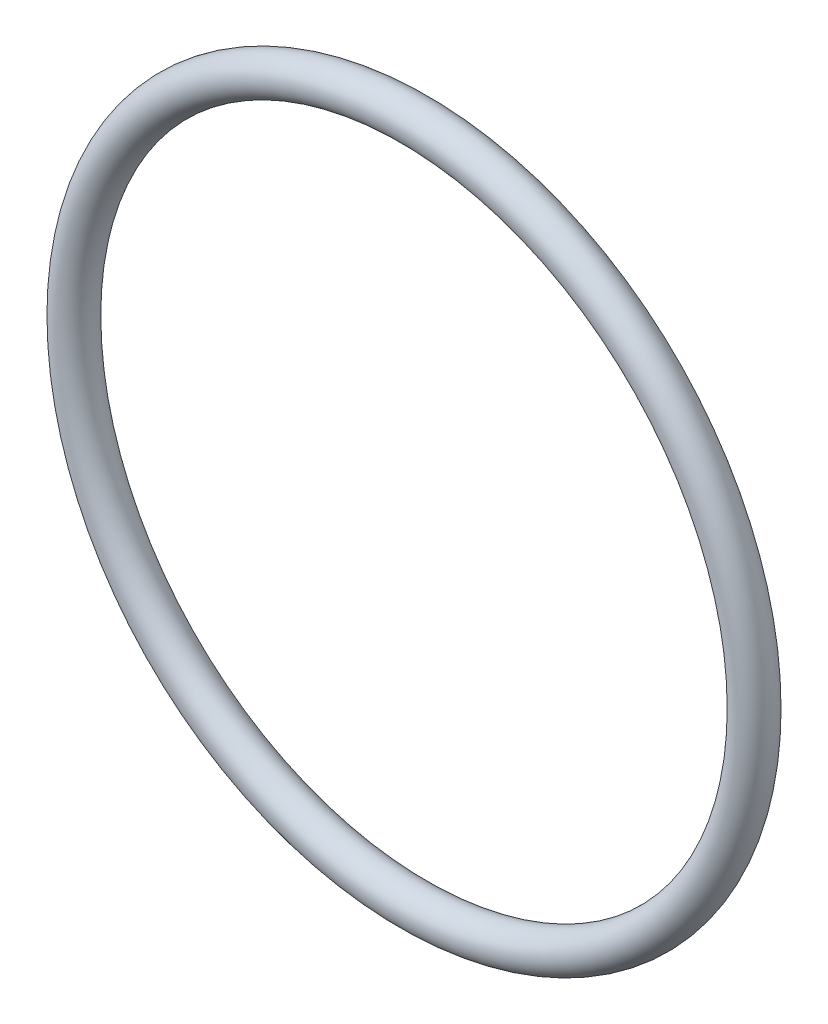
SolidWorks part; units mm, degrees
material "NBR"
ref_plane "Front Plane" through (0, 0, 0) normal (0, 0, 1) x (1, 0, 0)
ref_plane "Top Plane" through (0, 0, 0) normal (0, 1, 0) x (1, 0, 0)
ref_plane "Right Plane" through (0, 0, 0) normal (1, 0, 0) x (0, 0, -1)
sketch "Sketch1" plane through (0, 0, 0) normal (1, 0, 0) x (0, 0, -1)
  line L0 (-151.1552, 0) -> (-75.3028, 0) construction
  circle A0 centre (0, 15.875) radius 0.7937 construction
  circle A1 centre (0, 15.875) radius 0.889
  dimension "D3" = 1.778
  dimension "D1" = 30.1625
  dimension "D2" = 33.3375
revolve "Revolve1" add sketch "Sketch1" angle 360 about L0
